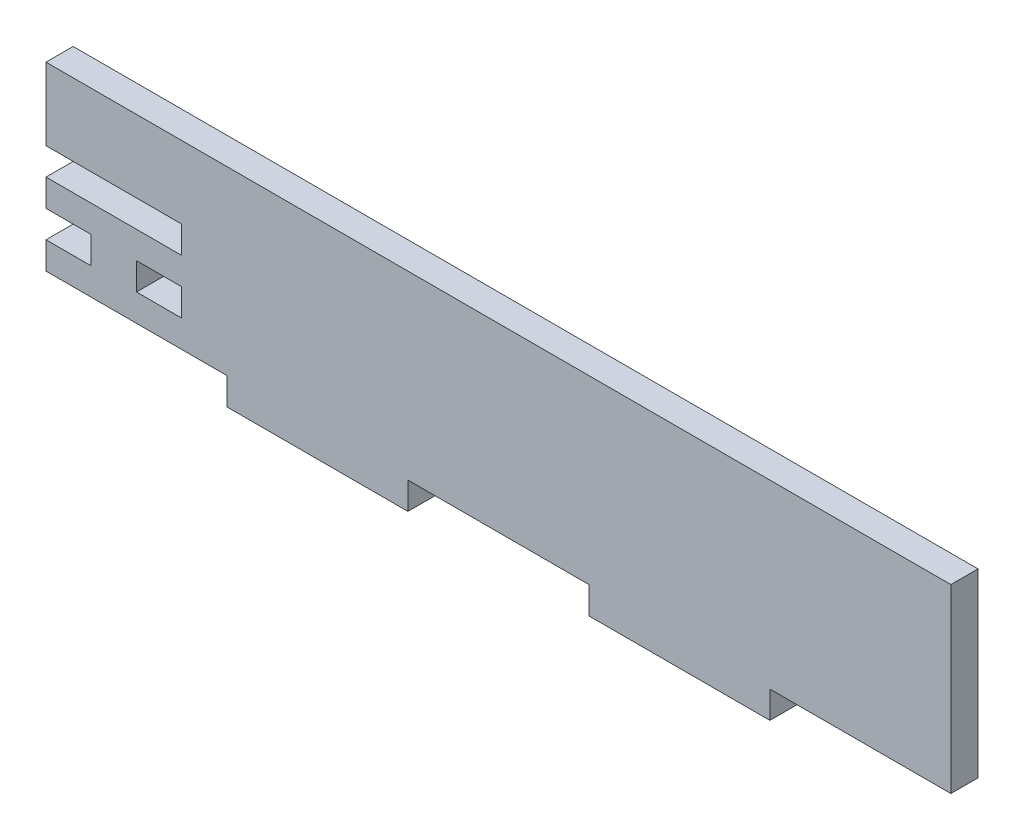
SolidWorks part; units mm, degrees
material "Pine"
ref_plane "Front Plane" through (0, 0, 0) normal (0, 0, 1) x (1, 0, 0)
ref_plane "Top Plane" through (0, 0, 0) normal (0, 1, 0) x (1, 0, 0)
ref_plane "Right Plane" through (0, 0, 0) normal (1, 0, 0) x (0, 0, -1)
sketch "Sketch1" plane through (0, 0, 0) normal (0, 0, 1) x (1, 0, 0)
  line L1 (-100, 23) -> (100, 23)
  line L2 (-100, 23) -> (-100, -23)
  line L3 (-100, -23) -> (100, -23)
  line L4 (100, 23) -> (100, -23)
  line L5 (-100, 23) -> (100, -23) construction
  line L6 (-100, -23) -> (100, 23) construction
  point P0 (0, 0)
  dimension "D1" = 46
  dimension "D2" = 200
extrude "Boss-Extrude1" add sketch "Sketch1" along normal blind 6
sketch "Sketch2" plane through (0, 0, 6) normal (0, 0, 1) x (1, 0, 0)
  line L0 (-20, -23) -> (-20, -17)
  line L1 (-100, -23) -> (-60, -23)
  line L2 (-100, -23) -> (-100, -17)
  line L3 (-100, -17) -> (-60, -17)
  line L4 (-60, -23) -> (-60, -17)
  line L5 (-20, -23) -> (20, -23)
  line L6 (20, -23) -> (20, -17)
  line L7 (-20, -17) -> (20, -17)
  line L8 (60, -23) -> (60, -17)
  line L9 (60, -23) -> (100, -23)
  line L10 (100, -23) -> (100, -17)
  line L11 (60, -17) -> (100, -17)
  dimension "D1" = 40
  dimension "D2" = 6
  dimension "D3" = 3
extrude "Cut-Extrude1" cut sketch "Sketch2" against normal blind 6
sketch "Sketch3" plane through (0, 0, 6) normal (0, 0, 1) x (1, 0, 0)
  line L0 (-100, 23) -> (-100, -17) construction
  line L1 (-100, -11) -> (-90, -11)
  line L2 (-100, -11) -> (-100, -5)
  line L3 (-100, -5) -> (-90, -5)
  line L4 (-90, -11) -> (-90, -5)
  line L5 (-60, -17) -> (-100, -17) construction
  line L6 (-80, -11) -> (-80, -5)
  line L7 (-80, -11) -> (-70, -11)
  line L8 (-70, -11) -> (-70, -5)
  line L9 (-80, -5) -> (-70, -5)
  dimension "D1" = 6
  dimension "D2" = 6
  dimension "D3" = 10
  dimension "D4" = 2
extrude "Cut-Extrude2" cut sketch "Sketch3" against normal blind 10
sketch "Sketch4" plane through (0, 0, 6) normal (0, 0, 1) x (1, 0, 0)
  line L0 (-100, 23) -> (-100, -5) construction
  line L1 (-100, 7) -> (-70, 7)
  line L2 (-100, 7) -> (-100, 1)
  line L3 (-100, 1) -> (-70, 1)
  line L4 (-70, 7) -> (-70, 1)
  line L5 (-90, -5) -> (-100, -5) construction
  dimension "D1" = 6
  dimension "D2" = 6
  dimension "D3" = 30
extrude "Cut-Extrude3" cut sketch "Sketch4" against normal blind 10
